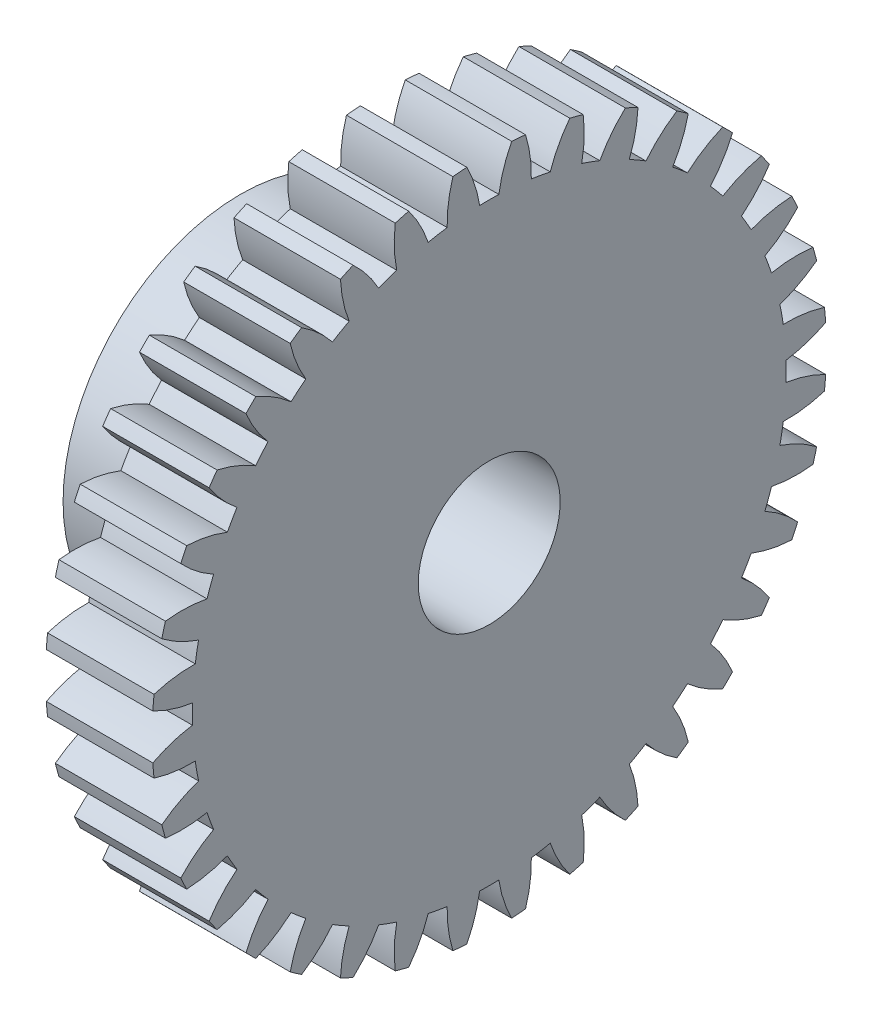
SolidWorks part; units mm, degrees
ref_plane "Plane1" through (0, 0, 0) normal (0, 0, 1) x (1, 0, 0)
ref_plane "Plane2" through (0, 0, 0) normal (0, 1, 0) x (1, 0, 0)
ref_plane "Plane3" through (0, 0, 0) normal (1, 0, 0) x (0, 0, -1)
other "Configuration Table"
sketch "HoldingSke" plane through (0, 0, 0) normal (0, 1, 0) x (1, 0, 0)
  line L0 (0, 0) -> (657.569, -477.7519)
  line L1 (-15, 0) -> (100, 0) construction
  line L2 (0, 0) -> (-2.1039, 2.3779)
  line L3 (0, 0) -> (-11.863, 4.5341)
  line L4 (0, 0) -> (6.9867, 5.0761)
  line L5 (0, 0) -> (-10.4238, -3.8878)
  line L6 (0, 0) -> (-3.9479, -2.6637)
  line L7 (-2.1039, 2.3779) -> (0.2908, 13.2423)
  line L8 (-76.2, 54.61) -> (-69.596, 54.61)
  line L9 (-67.7845, 28.3722) -> (-49.3413, 33.142)
  line L10 (-76.2, 71.12) -> (104.1128, 71.12)
  line L11 (0, 0) -> (-4.7625, 0)
  line L12 (-76.2, 101.6) -> (-76.1716, 101.6)
  line L13 (24.9733, 27.94) -> (52.9518, 28.4284)
  line L14 (24.9733, 27.94) -> (25.0241, 27.9398)
  line L15 (24.9733, 27.94) -> (100.4021, 29.52)
  circle A0 centre (0, 0) radius 3.175
  circle A1 centre (0, 0) radius 7.9375
  circle A2 centre (0, 0) radius 7.9375
  circle A3 centre (0, 0) radius 3.175
  dimension "MHD" = 15.875
  dimension "Hub_dia" = 15.875
  dimension "Bore" = 6.35
  dimension "MBD" = 6.35
  dimension "Num_teeth" = 36
  dimension "Pitch" = 812.8
  dimension "Overall_len" = 11.1252
  dimension "Show_teeth" = 36
  dimension "Thickness" = 4.7625
  dimension "OAL" = 11.1253
  dimension "T_dim" = 6.604
  dimension "Ap" = 14.5
  dimension "H" = 19.05
  dimension "Pitch_radius" = 180.3128
  dimension "Width" = 4.7625
  dimension "Backlash" = 0.0284
  dimension "Addendum_fac" = 1
  dimension "Dedendum_fac" = 1.2
  dimension "Clearance_fac" = 0.2
  dimension "Dedendum_add" = 0.0508
sketch "BasProSke" plane through (0, 0, 0) normal (0, 1, 0) x (1, 0, 0)
  line L0 (-10, 0) -> (60, 0) construction
  line L1 (0, 0) -> (0, 15.0812)
  line L2 (0, 0) -> (4.7625, 0)
  line L3 (4.7625, 0) -> (4.7625, 15.0812)
  line L4 (4.7625, 15.0812) -> (0, 15.0812)
  dimension "Thickness" = 4.7625
  dimension "Diameter" = 30.1625
revolve "Base-Revolve" add sketch "BasProSke" angle 360 about L0
sketch "TooCutSke" plane through (0, 0, 0) normal (1, 0, 0) x (0, 0, -1)
  line L1 (0, 0) -> (0, 107) construction
  line L2 (0, 0) -> (-0.673, 14.2716) construction
  line L3 (0, 0) -> (-2.4885, 28.4433) construction
  line L4 (-0.673, 14.2716) -> (-1.2442, 14.2217) construction
  arc A0 (0.4301, 13.2772) -> (-0.4301, 13.2772) centre (0, 0) ccw
  arc A1 (1.0168, 15.0724) -> (-1.0168, 15.0724) centre (0, 0) ccw
  circle A2 centre (0, 0) radius 14.2875 construction
  circle A3 centre (0, 0) radius 13.8324 construction
  arc A4 (-0.4301, 13.2772) -> (-1.0168, 15.0724) centre (-6.0811, 12.424) ccw
  arc A5 (1.0168, 15.0724) -> (0.4301, 13.2772) centre (6.0811, 12.424) ccw
  dimension "Root_dia" = 26.5684
  dimension "Overcut_dia" = 30.2133
  dimension "Pitch_dia" = 28.575
  dimension "Base_dia" = 27.6648
  dimension "Flank_rad" = 5.715
  dimension "Half_ang" = 5
  dimension "Half_CT" = 0.5734
extrude "ToothCut" cut sketch "TooCutSke" along normal through all
fillet "Breaks" [suppressed] radius 0.0159
fillet "RootFillets" [suppressed] radius 0.2095
pattern_circular "TeethCuts" count 36 every 10 about axis through (-10, 0, 0) along (1, 0, 0) of "ToothCut", "RootFillets", "Breaks"
sketch "HubNeaOneSke" plane through (0, 0, 0) normal (-1, 0, 0) x (0, 0, 1)
  circle A0 centre (0, 0) radius 7.9375
  dimension "Diameter" = 15.875
extrude "HubNearOne" add sketch "HubNeaOneSke" along normal blind 6.3628
sketch "HubNeaBotSke" plane through (0, 0, 0) normal (-1, 0, 0) x (0, 0, 1)
  circle A0 centre (0, 0) radius 7.9375
  dimension "Diameter" = 15.875
extrude "HubNearBoth" [suppressed] add sketch "HubNeaBotSke" along normal blind 3.1814
ref_plane "FarPln" through (4.7625, 0, 0) normal (1, 0, 0) x (0, 0, -1)
sketch "HubFarSke" plane through (4.7625, 0, 0) normal (1, 0, 0) x (0, 0, -1)
  circle A0 centre (0, 0) radius 7.9375
  dimension "Diameter" = 15.875
extrude "HubFar" [suppressed] add sketch "HubFarSke" along normal blind 3.1814
sketch "BorSke" plane through (0, 0, 0) normal (1, 0, 0) x (0, 0, -1)
  circle A0 centre (0, 0) radius 3.175
  dimension "Diameter" = 6.35
extrude "Bore" cut sketch "BorSke" along normal mid plane 22.2505
sketch "KeySke" plane through (0, 0, 0) normal (1, 0, 0) x (0, 0, -1)
  line L0 (-0.127, 0) -> (-0.127, 3.429)
  line L1 (-0.127, 3.429) -> (0.127, 3.429)
  line L2 (0.127, 3.429) -> (0.127, 0)
  line L3 (0, 0) -> (0, 34) construction
  line L4 (-0.127, 0) -> (0.127, 0)
  dimension "Offset" = 3.429
  dimension "Width" = 0.254
extrude "Keyway" [suppressed] cut sketch "KeySke" along normal mid plane 22.2505
pattern_circular "Keyway2" [suppressed] count 2 every 90 about axis through (-10, 0, 0) along (1, 0, 0)
equation "' \"Pitch@HoldingSke\" = 4"
equation "' \"Num_teeth@HoldingSke\" = 12"
equation "' \"Ap@HoldingSke\" =  20"
equation "' \"Ap@HoldingSke\" = 20"
equation "' \"Width@HoldingSke\" = 0.5"
equation "' \"Hub_dia@HoldingSke\"= 1"
equation "' \"Hub_dia@HoldingSke\" = 1"
equation "' \"Overall_len@HoldingSke\" = 1.0"
equation "' \"Bore@HoldingSke\" = 0.75"
equation "' \"T_dim@HoldingSke\" = 0.85"
equation "' \"Width@KeySke\" = 0.25"
equation "' \"Show_teeth@HoldingSke\" = 13"
equation "' \"Backlash@HoldingSke\" = 0.009"
equation "' \"Addendum_fac@HoldingSke\" = 1.0"
equation "' \"Dedendum_fac@HoldingSke\" = 1.25"
equation "' \"Dedendum_add@HoldingSke\" = 0.00005"
equation "' \"Clearance_fac@HoldingSke\" = 0.25"
equation "' \"Pitch@HoldingSke\" = 0.5"
equation "' \"Num_teeth@HoldingSke\" = 23"
equation "' \"Show_teeth@HoldingSke\" = 23"
equation "' \"Backlash@HoldingSke\" = 0.0375"
equation "\"Overcut_dia@TooCutSke\" = (\"Num_teeth@HoldingSke\" + 2 * \"Addendum_fac@HoldingSke\") / \"Pitch@HoldingSke\" + 0.002"
equation "\"Pitch_dia@TooCutSke\" = \"Num_teeth@HoldingSke\" / \"Pitch@HoldingSke\""
equation "\"Base_dia@TooCutSke\" = \"Num_teeth@HoldingSke\" / \"Pitch@HoldingSke\" * cos((\"Ap@HoldingSke\"  * 3.14159265 / 180))"
equation "\"Root_dia@TooCutSke\" = (\"Num_teeth@HoldingSke\" + 2) / \"Pitch@HoldingSke\" - 2 * (\"Addendum_fac@HoldingSke\" + \"Dedendum_fac@HoldingSke\") / \"Pitch@HoldingSke\" - \"Dedendum_add@HoldingSke\" * 2"
equation "\"Half_ang@TooCutSke\" = 180 / \"Num_teeth@HoldingSke\""
equation "\"Half_CT@TooCutSke\" = \"Num_teeth@HoldingSke\" / \"Pitch@HoldingSke\" * sin((3.14159265 / 2 / \"Num_teeth@HoldingSke\")) / 2 - 7 * \"Backlash@HoldingSke\" / 4"
equation "\"Flank_rad@TooCutSke\" = \"Num_teeth@HoldingSke\" / \"Pitch@HoldingSke\" / 5"
equation "\"Radius@RootFillets\" = \"Clearance_fac@HoldingSke\" / \"Pitch@HoldingSke\" + \"Dedendum_add@HoldingSke\""
equation "\"Break_rad@Breaks\" = 0.02 / \"Pitch@HoldingSke\""
equation "\"Thickness@HoldingSke\" = \"Width@HoldingSke\""
equation "\"OAL@HoldingSke\" = \"Thickness@HoldingSke\""
equation "\"MHD@HoldingSke\" = (\"Num_teeth@HoldingSke\" + 2) / \"Pitch@HoldingSke\" - 2 * (\"Addendum_fac@HoldingSke\" + \"Dedendum_fac@HoldingSke\")  / \"Pitch@HoldingSke\" - \"Dedendum_add@HoldingSke\" * 2"
equation "\"MBD@HoldingSke\" = (\"Num_teeth@HoldingSke\" + 2) / \"Pitch@HoldingSke\" - 2 * (\"Addendum_fac@HoldingSke\" + \"Dedendum_fac@HoldingSke\")  / \"Pitch@HoldingSke\" - \"Dedendum_add@HoldingSke\" * 2 - 0.002"
equation "\"MHD@HoldingSke\" = ((sgn( \"MHD@HoldingSke\" - \"Hub_dia@HoldingSke\" )-1)*( \"MHD@HoldingSke\" - \"Hub_dia@HoldingSke\" ))/-2+ \"Hub_dia@HoldingSke\""
equation "\"MBD@HoldingSke\" = ((sgn( \"MBD@HoldingSke\" - \"Bore@HoldingSke\" )-1)*( \"MBD@HoldingSke\" - \"Bore@HoldingSke\" ))/-2+ \"Bore@HoldingSke\""
equation "\"OAL@HoldingSke\" = ((sgn( \"OAL@HoldingSke\" - \"Overall_len@HoldingSke\" )+1)*( \"OAL@HoldingSke\" - \"Overall_len@HoldingSke\" ))/2 + \"Overall_len@HoldingSke\" + 0.000002"
equation "\"Num_teeth@TeethCuts\" = int( \"Show_teeth@HoldingSke\" ) + 1"
equation "\"Num_teeth@TeethCuts\" = ((sgn( \"Num_teeth@TeethCuts\" - \"Num_teeth@HoldingSke\" )-1)*( \"Num_teeth@TeethCuts\" - \"Num_teeth@HoldingSke\" ))/-2+ \"Num_teeth@HoldingSke\""
equation "\"Num_teeth@TeethCuts\" = ((sgn( \"Num_teeth@TeethCuts\" - 2.0)+1)*( \"Num_teeth@TeethCuts\" - 2.0))/2 +2.0"
equation "\"Angle@TeethCuts\" = 360.0 / \"Num_teeth@HoldingSke\""
equation "\"Diameter@BasProSke\" = (\"Num_teeth@HoldingSke\" + 2 * \"Addendum_fac@HoldingSke\") / \"Pitch@HoldingSke\""
equation "\"Thickness@BasProSke\"  = \"Thickness@HoldingSke\""
equation "' \"Fillet_rad@BasProSke\" =  \"Thickness@HoldingSke\" * 0.05"
equation "' \"Fillet_rad@BasProSke\" = \"Thickness@HoldingSke\" * 0.05"
equation "\"MHD@HoldingSke\" = ((sgn( \"MHD@HoldingSke\" - \"Root_dia@TooCutSke\" )-1)*( \"MHD@HoldingSke\" - \"Root_dia@TooCutSke\" ))/-2+ \"Root_dia@TooCutSke\""
equation "\"Diameter@HubNeaOneSke\" = \"MHD@HoldingSke\""
equation "\"Length@HubNearOne\" = \"OAL@HoldingSke\" - \"Thickness@BasProSke\""
equation "\"Diameter@HubNeaBotSke\" = \"MHD@HoldingSke\""
equation "\"Length@HubNearBoth\" = ( \"OAL@HoldingSke\" - \"Thickness@BasProSke\" ) / 2.0"
equation "\"Thickness@FarPln\" = \"Thickness@BasProSke\""
equation "\"Diameter@HubFarSke\" = \"MHD@HoldingSke\""
equation "\"Length@HubFar\" = ( \"OAL@HoldingSke\" - \"Thickness@BasProSke\" ) / 2.0"
equation "\"Diameter@BorSke\" = \"MBD@HoldingSke\""
equation "\"D1@Bore\" = \"OAL@HoldingSke\" * 2.0"
equation "\"D1@Keyway\" = \"OAL@HoldingSke\" * 2.0"
equation "\"Offset@KeySke\" = \"T_dim@HoldingSke\" - \"MBD@HoldingSke\" / 2.0"
